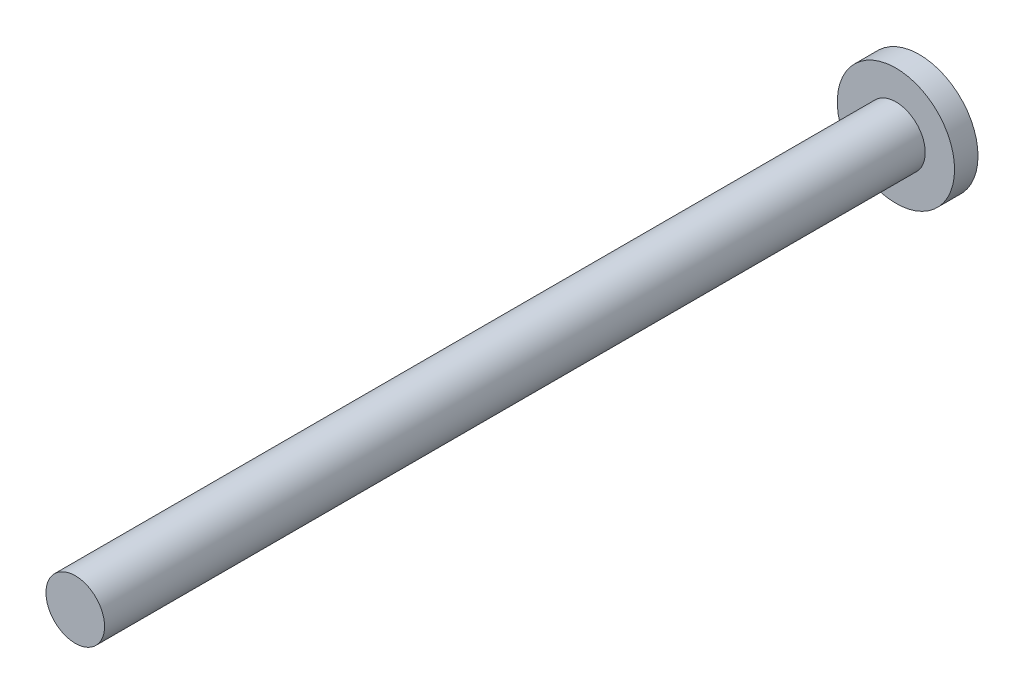
SolidWorks part; units mm, degrees
ref_plane "Front Plane" through (0, 0, 0) normal (0, 0, 1) x (1, 0, 0)
ref_plane "Top Plane" through (0, 0, 0) normal (0, 1, 0) x (1, 0, 0)
ref_plane "Right Plane" through (0, 0, 0) normal (1, 0, 0) x (0, 0, -1)
sketch "Sketch1" plane through (0, 0, 0) normal (0, 1, 0) x (1, 0, 0)
  line L0 (0, 0) -> (0, 72)
  line L1 (0, 72) -> (5, 72)
  line L2 (5, 72) -> (5, 70)
  line L3 (5, 70) -> (2.5, 70)
  line L4 (2.5, 70) -> (2.5, 0)
  line L5 (2.5, 0) -> (0, 0)
  dimension "D1" = 70
  dimension "D2" = 2
  dimension "D3" = 2.5
  dimension "D4" = 5
revolve "Revolve1" add sketch "Sketch1" angle 360 about L0
